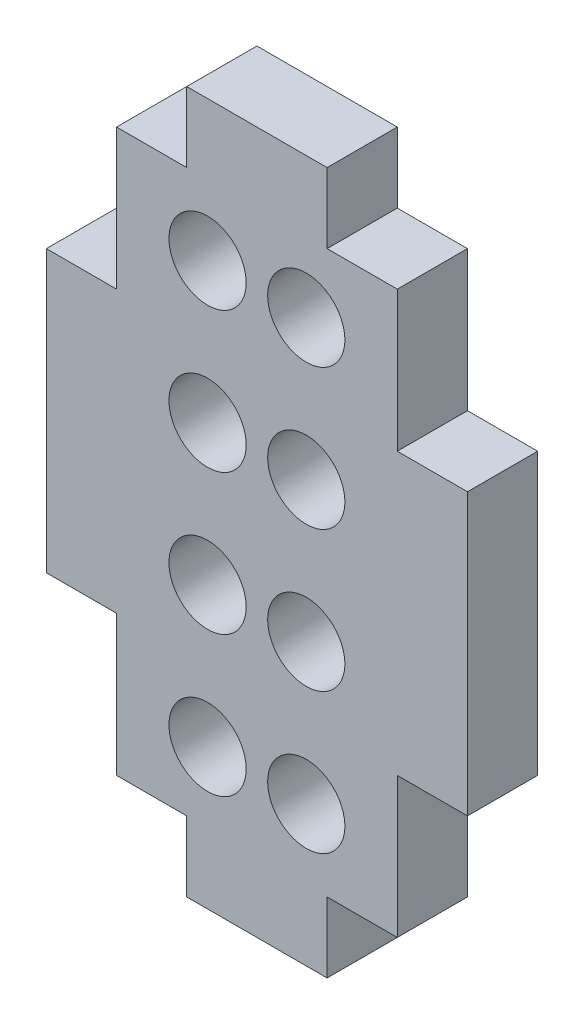
SolidWorks part; units mm, degrees
ref_plane "Front Plane" through (0, 0, 0) normal (0, 0, 1) x (1, 0, 0)
ref_plane "Top Plane" through (0, 0, 0) normal (0, 1, 0) x (1, 0, 0)
ref_plane "Right Plane" through (0, 0, 0) normal (1, 0, 0) x (0, 0, -1)
sketch "Sketch1" plane through (0, 0, 0) normal (0, 0, 1) x (1, 0, 0)
  line L0 (22.999, 20.5153) -> (32.999, 20.5153)
  line L1 (42.999, 5.5153) -> (42.999, -14.4847)
  line L2 (12.999, -14.4847) -> (12.999, 5.5153)
  line L3 (17.999, 5.5153) -> (17.999, 15.5153)
  line L4 (17.999, 15.5153) -> (22.999, 15.5153)
  line L5 (32.999, 15.5153) -> (37.999, 15.5153)
  line L6 (37.999, 5.5153) -> (37.999, 15.5153)
  line L7 (37.999, -14.4847) -> (37.999, -24.4847)
  line L8 (37.999, -24.4847) -> (32.999, -24.4847)
  line L9 (22.999, -24.4847) -> (17.999, -24.4847)
  line L10 (17.999, -24.4847) -> (17.999, -14.4847)
  line L11 (22.999, -29.4847) -> (32.999, -29.4847)
  line L33 (12.999, 5.5153) -> (17.999, 5.5153)
  line L37 (22.999, 15.5153) -> (22.999, 20.5153)
  line L43 (32.999, 20.5153) -> (32.999, 15.5153)
  line L45 (37.999, 5.5153) -> (42.999, 5.5153)
  line L51 (42.999, -14.4847) -> (37.999, -14.4847)
  line L55 (32.999, -24.4847) -> (32.999, -29.4847)
  line L57 (22.999, -29.4847) -> (22.999, -24.4847)
  line L63 (17.999, -14.4847) -> (12.999, -14.4847)
extrude "Boss-Extrude1" add sketch "Sketch1" along normal blind 5
sketch "Sketch2" plane through (0, 0, 5) normal (0, 0, 1) x (1, 0, 0)
  line L2 (27.999, 15.5153) -> (27.999, 11.0577) construction
  line L3 (24.4839, 15.5153) -> (24.4839, 9.2656) construction
  circle A0 centre (24.4839, 10.5153) radius 2.75
  circle A1 centre (24.4839, 0.5153) radius 2.75
  circle A2 centre (24.4839, -9.4847) radius 2.75
  circle A3 centre (24.4839, -19.4847) radius 2.75
  circle A4 centre (31.5141, -19.4847) radius 2.75
  circle A5 centre (31.5141, -9.4847) radius 2.75
  circle A6 centre (31.5141, 0.5153) radius 2.75
  circle A7 centre (31.5141, 10.5153) radius 2.75
  dimension "D1" = 5.5
  dimension "D3" = 4
extrude "Cut-Extrude1" cut sketch "Sketch2" against normal through all
